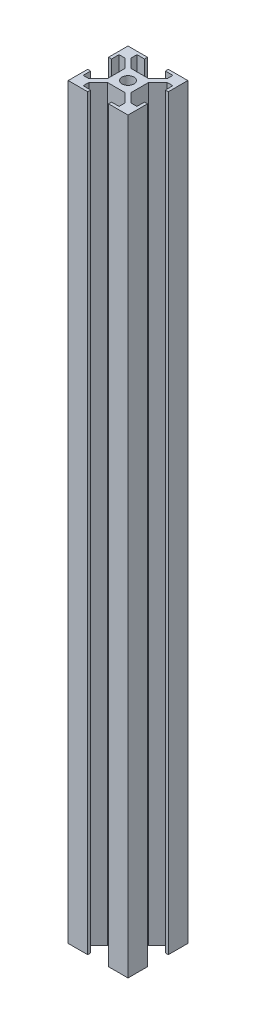
SolidWorks part; units mm, degrees
ref_plane "Front Plane" through (0, 0, 0) normal (0, 0, 1) x (1, 0, 0)
ref_plane "Top Plane" through (0, 0, 0) normal (0, 1, 0) x (1, 0, 0)
ref_plane "Right Plane" through (0, 0, 0) normal (1, 0, 0) x (0, 0, -1)
sketch "Sketch1" plane through (0, 0, 0) normal (0, 1, 0) x (1, 0, 0)
  line L1 (-20, -20) -> (20, -20)
  line L2 (-20, -20) -> (-20, 20)
  line L3 (-20, 20) -> (20, 20)
  line L4 (20, -20) -> (20, 20)
  line L5 (-20, -20) -> (20, 20) construction
  line L6 (-20, 20) -> (20, -20) construction
  point P0 (0, 0)
  dimension "D1" = 40
  dimension "D2" = 40
extrude "Boss-Extrude1" add sketch "Sketch1" along normal blind 500
sketch "Sketch2" plane through (0, 500, 0) normal (0, 1, 0) x (1, 0, 0)
  line L0 (0, 20) -> (0, -20) construction
  line L1 (20, 20) -> (-20, 20) construction
  line L2 (-20, -20) -> (20, -20) construction
  line L3 (-7, 20) -> (-7, 18)
  line L4 (-7, 18) -> (-12, 18)
  line L5 (-12, 18) -> (-12, 14.1213)
  line L6 (-12, 14.1213) -> (-5.8787, 8)
  line L7 (-5.8787, 8) -> (5.8787, 8)
  line L8 (-20, 20) -> (0, 0) construction
  line L9 (12, 14.1213) -> (5.8787, 8)
  line L10 (12, 18) -> (12, 14.1213)
  line L11 (7, 18) -> (12, 18)
  line L12 (7, 20) -> (7, 18)
  line L13 (20, 7) -> (18, 7)
  line L14 (18, 7) -> (18, 12)
  line L15 (18, 12) -> (14.1213, 12)
  line L16 (14.1213, 12) -> (8, 5.8787)
  line L17 (8, 5.8787) -> (8, -5.8787)
  line L18 (14.1213, -12) -> (8, -5.8787)
  line L19 (18, -12) -> (14.1213, -12)
  line L20 (18, -7) -> (18, -12)
  line L21 (20, -7) -> (18, -7)
  line L22 (7, -20) -> (7, -18)
  line L23 (7, -18) -> (12, -18)
  line L24 (12, -18) -> (12, -14.1213)
  line L25 (12, -14.1213) -> (5.8787, -8)
  line L26 (5.8787, -8) -> (-5.8787, -8)
  line L27 (-12, -14.1213) -> (-5.8787, -8)
  line L28 (-12, -18) -> (-12, -14.1213)
  line L29 (-7, -18) -> (-12, -18)
  line L30 (-7, -20) -> (-7, -18)
  line L31 (-20, -7) -> (-18, -7)
  line L32 (-18, -7) -> (-18, -12)
  line L33 (-18, -12) -> (-14.1213, -12)
  line L34 (-14.1213, -12) -> (-8, -5.8787)
  line L35 (-8, -5.8787) -> (-8, 5.8787)
  line L36 (-14.1213, 12) -> (-8, 5.8787)
  line L37 (-18, 12) -> (-14.1213, 12)
  line L38 (-18, 7) -> (-18, 12)
  line L39 (-20, 7) -> (-18, 7)
  line L40 (-20, 7) -> (-20, -7)
  line L41 (-7, 20) -> (7, 20)
  line L42 (20, 7) -> (20, -7)
  line L43 (-7, -20) -> (7, -20)
  circle A0 centre (0, 0) radius 4
  point P16 (0, 8)
  point P22 (0, 8)
  point P56 (0, 0)
  dimension "D7" = 8
  dimension "D1" = 7
  dimension "D2" = 12
  dimension "D3" = 2
  dimension "D4" = 5
  dimension "D5" = 1.5
  dimension "D6" = 4
extrude "Cut-Extrude1" cut sketch "Sketch2" against normal through all both and the other way through all
